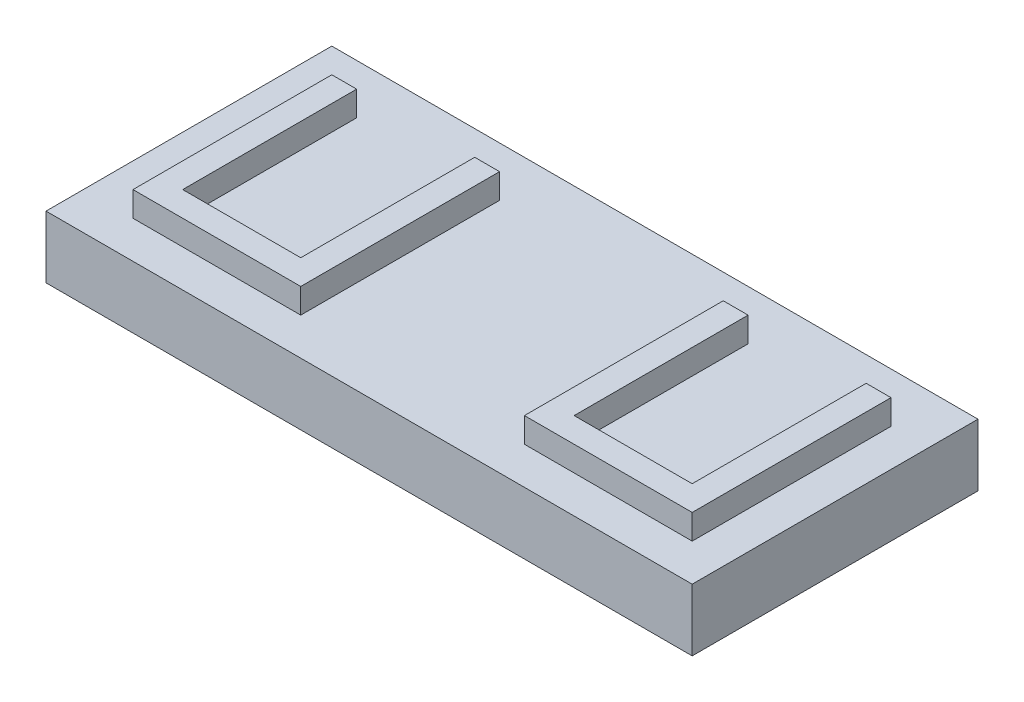
SolidWorks part; units mm, degrees
ref_plane "Front Plane" through (0, 0, 0) normal (0, 0, 1) x (1, 0, 0)
ref_plane "Top Plane" through (0, 0, 0) normal (0, 1, 0) x (1, 0, 0)
ref_plane "Right Plane" through (0, 0, 0) normal (1, 0, 0) x (0, 0, -1)
sketch "Sketch1" plane through (0, 0, 0) normal (0, 1, 0) x (1, 0, 0)
  line L1 (0, 0) -> (52, 0)
  line L2 (0, 0) -> (0, 23)
  line L3 (0, 23) -> (52, 23)
  line L4 (52, 0) -> (52, 23)
extrude "Boss-Extrude1" add sketch "Sketch1" along normal blind 5
sketch "Sketch2" plane through (0, 5, 0) normal (0, 1, 0) x (1, 0, 0)
  line L0 (47, 5) -> (37.5, 5)
  line L1 (37.5, 5) -> (37.5, 19)
  line L2 (37.5, 19) -> (35.5, 19)
  line L3 (35.5, 19) -> (35.5, 3)
  line L4 (35.5, 3) -> (49, 3)
  line L13 (47, 19) -> (47, 5)
  line L14 (47, 19) -> (49, 19)
  line L15 (49, 19) -> (49, 3)
  line L30 (4, 19) -> (4, 3)
  line L31 (6, 19) -> (4, 19)
  line L32 (6, 19) -> (6, 5)
  line L33 (17.5, 3) -> (4, 3)
  line L34 (17.5, 19) -> (17.5, 3)
  line L35 (15.5, 19) -> (17.5, 19)
  line L36 (15.5, 5) -> (15.5, 19)
  line L37 (6, 5) -> (15.5, 5)
extrude "Boss-Extrude2" add sketch "Sketch2" along normal blind 2
